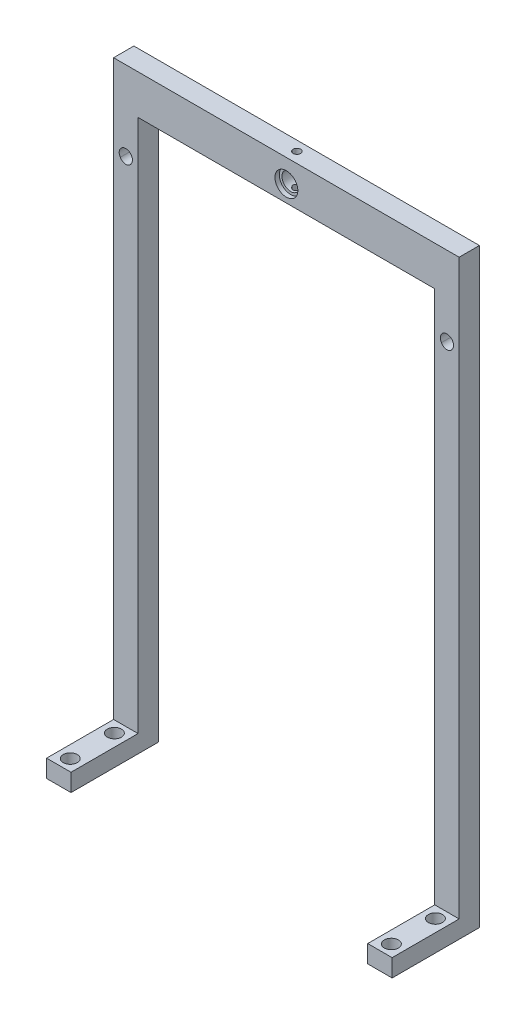
SolidWorks part; units mm, degrees
ref_plane "Front Plane" through (0, 0, 0) normal (0, 0, 1) x (1, 0, 0)
ref_plane "Top Plane" through (0, 0, 0) normal (0, 1, 0) x (1, 0, 0)
ref_plane "Right Plane" through (0, 0, 0) normal (1, 0, 0) x (0, 0, -1)
sketch "Sketch1" plane through (0, 0, 0) normal (0, 1, 0) x (1, 0, 0)
  line L1 (-157.2803, 56.7766) -> (-57.7377, 56.7766)
  line L2 (-157.2803, 56.7766) -> (-157.2803, 50.9346)
  line L3 (-157.2803, 50.9346) -> (-57.7377, 50.9346)
  line L4 (-57.7377, 56.7766) -> (-57.7377, 50.9346)
  dimension "D1" = 99.5426
  dimension "D2" = 5.842
extrude "Boss-Extrude1" add sketch "Sketch1" along normal blind 170.18
sketch "Sketch2" plane through (0, 0, -50.9346) normal (0, 0, 1) x (1, 0, 0)
  line L0 (-157.2803, 0) -> (-57.7377, 0) construction
  line L1 (-150.2445, 0) -> (-64.7735, 0)
  line L2 (-150.2445, 0) -> (-150.2445, 158.8)
  line L3 (-150.2445, 158.8) -> (-64.7735, 158.8)
  line L4 (-64.7735, 0) -> (-64.7735, 158.8)
  line L6 (-157.2803, 88.5539) -> (-150.2445, 88.5539) construction
  line L7 (-157.2803, 170.18) -> (-157.2803, 0) construction
  line L8 (-64.7735, 88.5539) -> (-57.7377, 88.5539) construction
  line L9 (-57.7377, 170.18) -> (-57.7377, 0) construction
  dimension "D1" = 158.8
  dimension "D2" = 85.471
extrude "Cut-Extrude1" cut sketch "Sketch2" against normal through all
sketch "Sketch3" plane through (0, 0, -50.9346) normal (0, 0, 1) x (1, 0, 0)
  line L0 (-150.2445, 158.8) -> (-150.2445, 0) construction
  line L1 (-157.2803, 0) -> (-150.2445, 0)
  line L2 (-157.2803, 0) -> (-157.2803, 5.08)
  line L3 (-157.2803, 5.08) -> (-150.2445, 5.08)
  line L4 (-150.2445, 0) -> (-150.2445, 5.08)
  line L5 (-57.7377, 170.18) -> (-57.7377, 0) construction
  line L6 (-64.7735, 0) -> (-57.7377, 0)
  line L7 (-64.7735, 0) -> (-64.7735, 5.08)
  line L8 (-64.7735, 5.08) -> (-57.7377, 5.08)
  line L9 (-57.7377, 0) -> (-57.7377, 5.08)
  dimension "D1" = 5.08
extrude "Boss-Extrude2" add sketch "Sketch3" along normal blind 19.304
sketch "Sketch4" plane through (0, 5.08, 0) normal (0, 1, 0) x (1, 0, 0)
  line L0 (-157.2803, 34.9326) -> (-153.7624, 34.9326) construction
  line L1 (-157.2803, 31.6306) -> (-157.2803, 50.9346) construction
  line L2 (-153.7624, 34.9326) -> (-150.2445, 34.9326) construction
  line L3 (-150.2445, 31.6306) -> (-150.2445, 50.9346) construction
  line L4 (-64.7735, 34.9326) -> (-61.2556, 34.9326) construction
  line L5 (-64.7735, 31.6306) -> (-64.7735, 50.9346) construction
  line L6 (-61.2556, 34.9326) -> (-57.7377, 34.9326) construction
  line L7 (-57.7377, 31.6306) -> (-57.7377, 50.9346) construction
  line L9 (-57.7377, 31.6306) -> (-64.7735, 31.6306) construction
  line L10 (-61.2556, 31.6306) -> (-61.2556, 34.9326) construction
  line L11 (-61.2556, 34.9326) -> (-61.2556, 47.6326) construction
  line L12 (-61.2556, 47.6326) -> (-61.2556, 50.9346) construction
  line L13 (-57.7377, 50.9346) -> (-64.7735, 50.9346) construction
  line L14 (-153.7624, 31.6306) -> (-153.7624, 34.9326) construction
  line L15 (-150.2445, 31.6306) -> (-157.2803, 31.6306) construction
  line L16 (-153.7624, 34.9326) -> (-153.7624, 47.6326) construction
  line L17 (-153.7624, 47.6326) -> (-153.7624, 50.9346) construction
  line L18 (-150.2445, 50.9346) -> (-157.2803, 50.9346) construction
  circle A0 centre (-153.7624, 34.9326) radius 2.032
  circle A1 centre (-153.7624, 47.6326) radius 2.032
  circle A2 centre (-61.2556, 34.9326) radius 2.032
  circle A3 centre (-61.2556, 47.6326) radius 2.032
  dimension "D2" = 4.064
  dimension "D1" = 12.7
extrude "Cut-Extrude2" cut sketch "Sketch4" against normal through all
sketch "Sketch5" plane through (0, 0, -50.9346) normal (0, 0, 1) x (1, 0, 0)
  line L0 (-157.2803, 170.18) -> (-57.7377, 170.18) construction
  line L1 (-157.2803, 163.576) -> (-107.509, 163.576) construction
  line L2 (-157.2803, 170.18) -> (-157.2803, 5.08) construction
  line L3 (-107.509, 163.576) -> (-57.7377, 163.576) construction
  line L4 (-57.7377, 170.18) -> (-57.7377, 5.08) construction
  circle A0 centre (-107.509, 163.576) radius 2.54
  dimension "D1" = 6.604
  dimension "D2" = 5.08
extrude "Cut-Extrude3" cut sketch "Sketch5" against normal through all
sketch "Sketch7" plane through (0, 0, -50.9346) normal (0, 0, 1) x (1, 0, 0)
  circle A0 centre (-107.509, 163.576) radius 3.302
  circle A1 centre (-107.509, 163.576) radius 2.54 construction
  dimension "D1" = 6.604
extrude "Cut-Extrude4" cut sketch "Sketch7" against normal blind 1.27
sketch "Sketch9" plane through (0, 0, -50.9346) normal (0, 0, 1) x (1, 0, 0)
  line L0 (-157.2803, 147.37) -> (-153.7624, 147.37) construction
  line L1 (-157.2803, 170.18) -> (-157.2803, 5.08) construction
  line L2 (-153.7624, 147.37) -> (-150.2445, 147.37) construction
  line L3 (-150.2445, 158.8) -> (-150.2445, 5.08) construction
  line L4 (-150.2445, 147.37) -> (-64.7735, 147.37) construction
  line L5 (-64.7735, 5.08) -> (-64.7735, 158.8) construction
  line L6 (-64.7735, 147.37) -> (-61.2556, 147.37) construction
  line L7 (-61.2556, 147.37) -> (-57.7377, 147.37) construction
  line L8 (-57.7377, 170.18) -> (-57.7377, 5.08) construction
  line L9 (-64.7735, 158.8) -> (-150.2445, 158.8) construction
  circle A0 centre (-153.7624, 147.37) radius 1.905
  circle A1 centre (-61.2556, 147.37) radius 1.905
  dimension "D1" = 3.81
  dimension "D2" = 11.43
  dimension "D3" = 92.5068
sketch "Sketch10" plane through (0, 170.18, 0) normal (0, 1, 0) x (1, 0, 0)
  line L0 (-157.2803, 50.9346) -> (-57.7377, 50.9346) construction
  line L1 (-107.509, 53.9826) -> (-157.2803, 53.9826) construction
  line L3 (-107.509, 53.9826) -> (-57.7377, 53.9826) construction
  line L4 (-57.7377, 50.9346) -> (-57.7377, 56.7766) construction
  line L5 (-157.2803, 56.7766) -> (-157.2803, 50.9346) construction
  circle A0 centre (-107.509, 53.9826) radius 1.0795
  dimension "D1" = 2.159
  dimension "D2" = 3.048
extrude "Cut-Extrude7" cut sketch "Sketch10" against normal through all
sketch "Sketch11" plane through (0, 0, -50.9346) normal (0, 0, 1) x (1, 0, 0)
  line L0 (-157.2803, 147.116) -> (-153.7624, 147.116) construction
  line L1 (-157.2803, 170.18) -> (-157.2803, 5.08) construction
  line L2 (-153.7624, 147.116) -> (-150.2445, 147.116) construction
  line L3 (-150.2445, 158.8) -> (-150.2445, 5.08) construction
  line L4 (-150.2445, 147.116) -> (-64.7735, 147.116) construction
  line L5 (-64.7735, 5.08) -> (-64.7735, 158.8) construction
  line L6 (-64.7735, 147.116) -> (-61.2556, 147.116) construction
  line L7 (-61.2556, 147.116) -> (-57.7377, 147.116) construction
  line L8 (-57.7377, 170.18) -> (-57.7377, 5.08) construction
  line L11 (-64.7735, 158.8) -> (-150.2445, 158.8) construction
  circle A0 centre (-153.7624, 147.116) radius 1.778
  circle A1 centre (-61.2556, 147.116) radius 1.778
  dimension "D1" = 3.556
  dimension "D2" = 11.684
extrude "Cut-Extrude8" cut sketch "Sketch11" against normal through all
extrude "Cut-Extrude6" cut sketch "Sketch9" against normal through all
